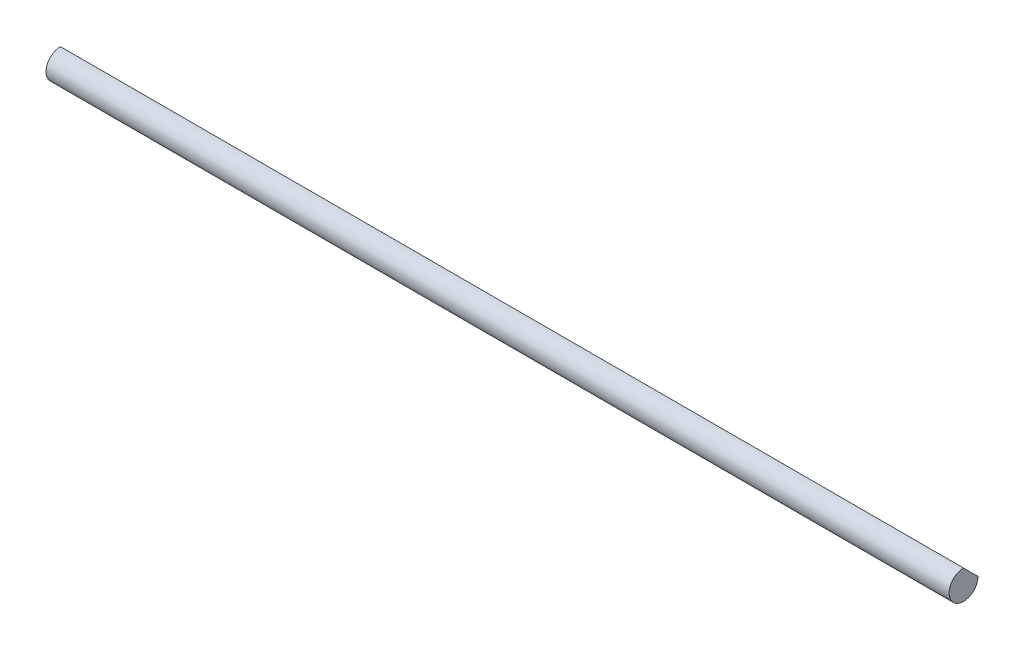
SolidWorks part; units mm, degrees
ref_plane "前视基准面" through (0, 0, 0) normal (0, 0, 1) x (1, 0, 0)
ref_plane "上视基准面" through (0, 0, 0) normal (0, 1, 0) x (1, 0, 0)
ref_plane "右视基准面" through (0, 0, 0) normal (1, 0, 0) x (0, 0, -1)
other "Configuration Table"
sketch "草图1" plane through (0, 0, 0) normal (1, 0, 0) x (0, 0, -1)
  line L0 (0, 2) -> (2, 0)
  arc A0 (0, 2) -> (2, 0) centre (0, 0) ccw
  dimension "D1" = 2
extrude "凸台-拉伸1" add sketch "草图1" along normal blind 125
